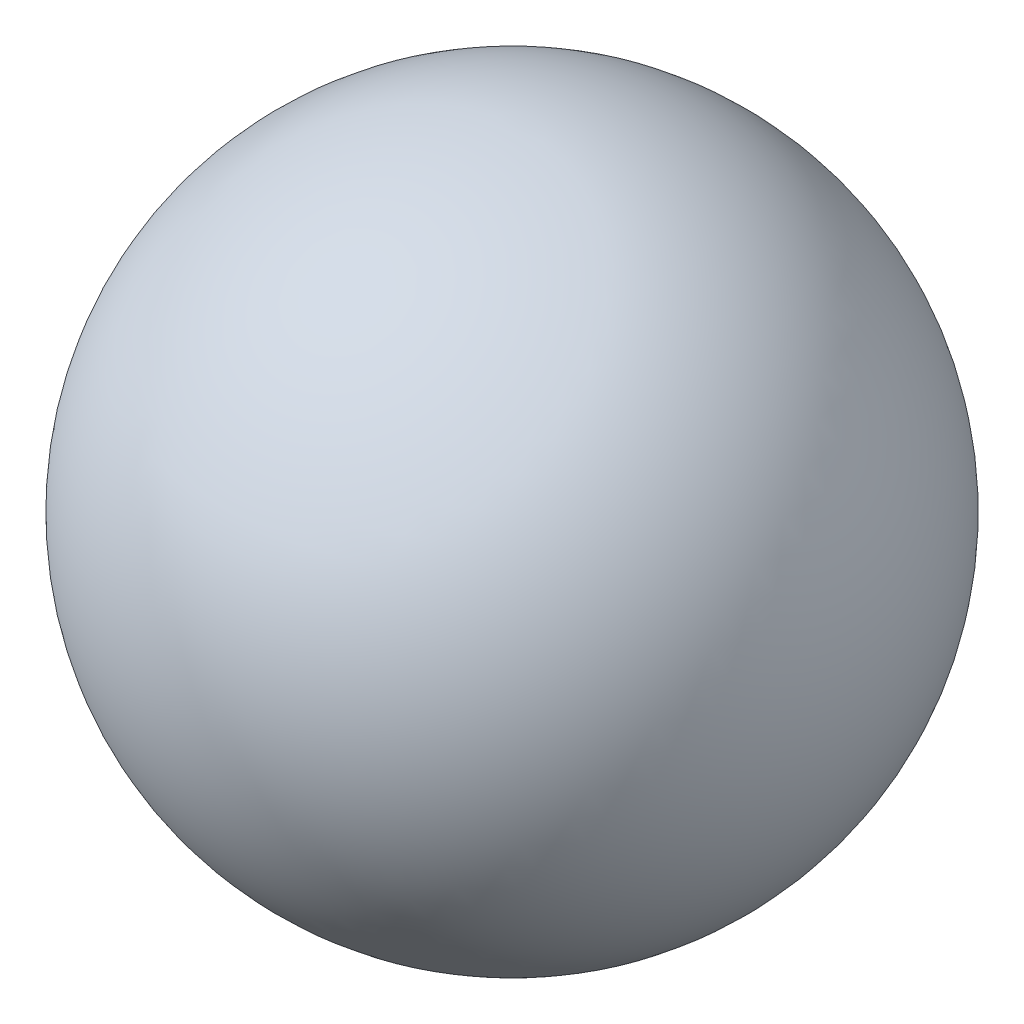
SolidWorks part; units mm, degrees
ref_plane "前基準面" through (0, 0, 0) normal (0, 0, 1) x (1, 0, 0)
ref_plane "上基準面" through (0, 0, 0) normal (0, 1, 0) x (1, 0, 0)
ref_plane "右基準面" through (0, 0, 0) normal (1, 0, 0) x (0, 0, -1)
sketch "草圖1" plane through (0, 0, 0) normal (0, 0, 1) x (1, 0, 0)
  line L0 (0, 30) -> (0, -30)
  arc A0 (0, -30) -> (0, 30) centre (0, 0) ccw
  dimension "D1" = 60
revolve "旋轉1" add sketch "草圖1" angle 360 about L0
